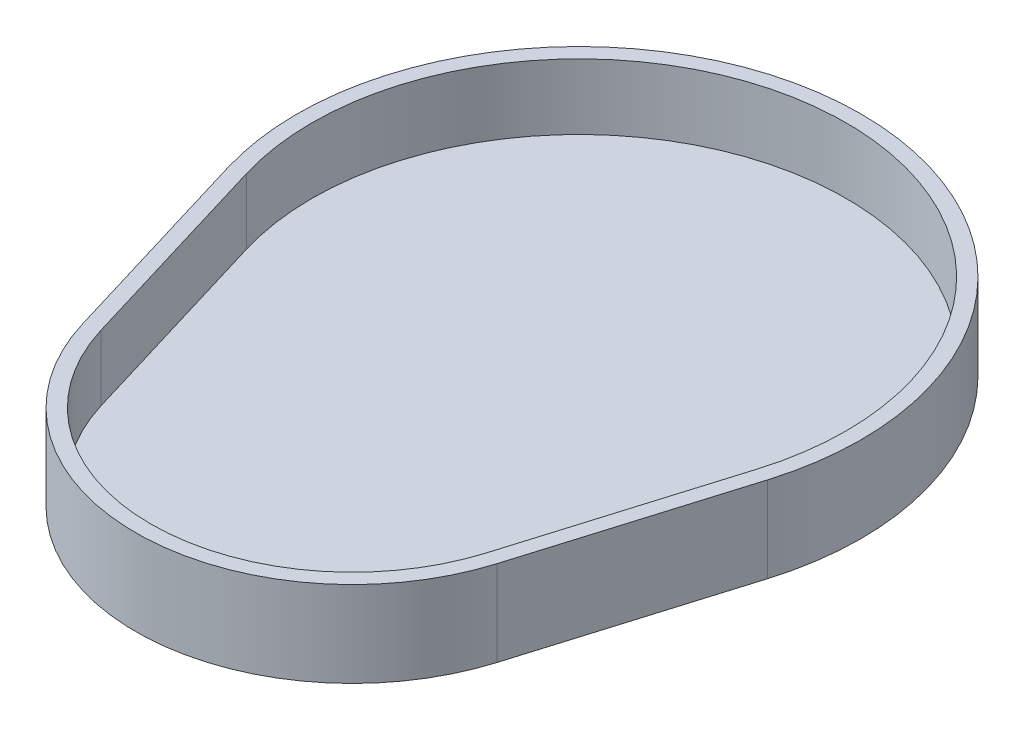
SolidWorks part; units mm, degrees
ref_plane "Alzado" through (0, 0, 0) normal (0, 0, 1) x (1, 0, 0)
ref_plane "Planta" through (0, 0, 0) normal (0, 1, 0) x (1, 0, 0)
ref_plane "Vista lateral" through (0, 0, 0) normal (1, 0, 0) x (0, 0, -1)
sketch "Croquis1" plane through (0, 0, 0) normal (0, 1, 0) x (1, 0, 0)
  line L0 (-53.6123, -2.1778) -> (-41.1666, -43.4222)
  line L1 (41.1666, -43.4222) -> (53.6123, -2.1778)
  arc A0 (-41.1666, -43.4222) -> (41.1666, -43.4222) centre (0, -31) ccw
  arc A1 (53.6123, -2.1778) -> (-53.6123, -2.1778) centre (0, 14) ccw
  dimension "D1" = 14
  dimension "D3" = 56
  dimension "D4" = 43
  dimension "D2" = 45
extrude "Saliente-Extruir1" add sketch "Croquis1" along normal blind 4
sketch "Croquis3" plane through (0, 4, 0) normal (0, 1, 0) x (1, 0, 0)
  line L0 (41.1666, -43.4222) -> (53.6123, -2.1778) construction
  line L1 (-53.6123, -2.1778) -> (-41.1666, -43.4222) construction
  line L2 (41.1666, -43.4222) -> (53.6123, -2.1778)
  line L3 (-53.6123, -2.1778) -> (-41.1666, -43.4222)
  line L4 (38.2945, -42.5556) -> (50.7402, -1.3111)
  line L5 (-50.7402, -1.3111) -> (-38.2945, -42.5556)
  arc A0 (-41.1666, -43.4222) -> (41.1666, -43.4222) centre (0, -31) ccw construction
  arc A1 (53.6123, -2.1778) -> (-53.6123, -2.1778) centre (0, 14) ccw construction
  arc A2 (-41.1666, -43.4222) -> (41.1666, -43.4222) centre (0, -31) ccw
  arc A3 (53.6123, -2.1778) -> (-53.6123, -2.1778) centre (0, 14) ccw
  arc A4 (50.7402, -1.3111) -> (-50.7402, -1.3111) centre (0, 14) ccw
  arc A5 (-38.2945, -42.5556) -> (38.2945, -42.5556) centre (0, -31) ccw
  dimension "D1" = 3
extrude "Saliente-Extruir3" add sketch "Croquis3" along normal blind 13
